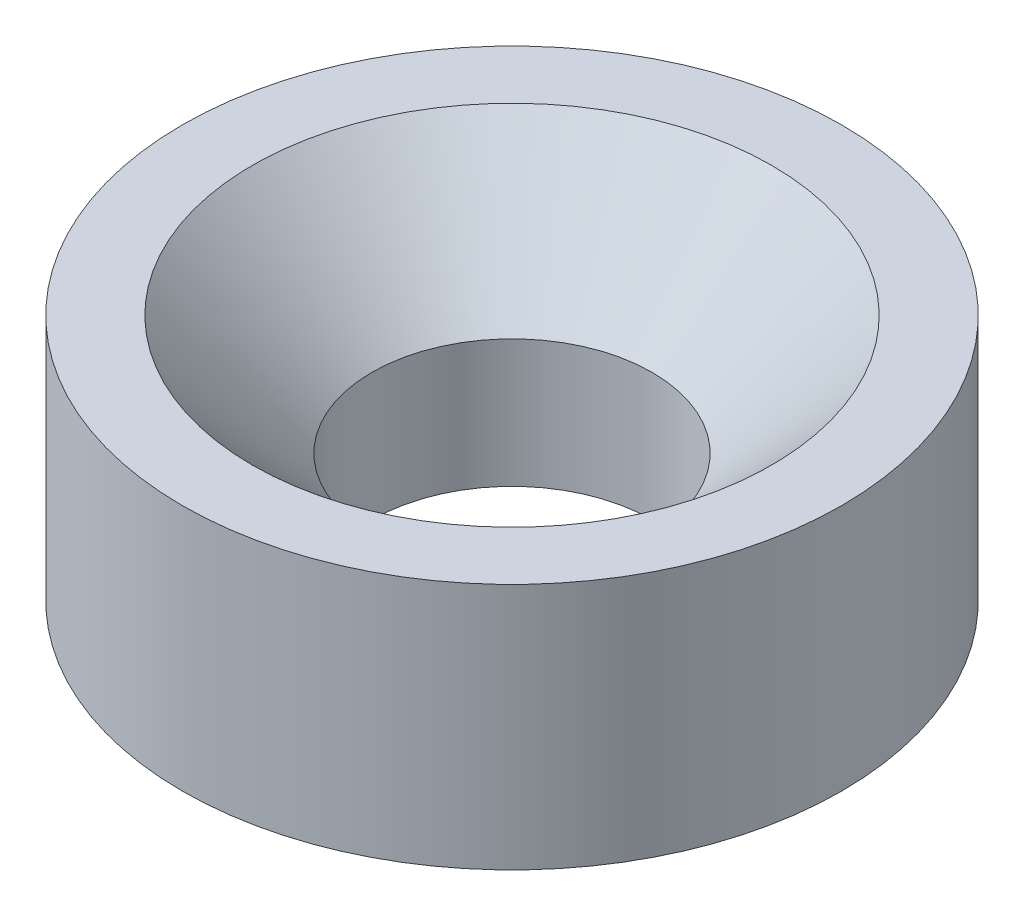
SolidWorks part; units mm, degrees
ref_plane "Front Plane" through (0, 0, 0) normal (0, 0, 1) x (1, 0, 0)
ref_plane "Top Plane" through (0, 0, 0) normal (0, 1, 0) x (1, 0, 0)
ref_plane "Right Plane" through (0, 0, 0) normal (1, 0, 0) x (0, 0, -1)
sketch "Sketch1" plane through (0, 0, 0) normal (0, 1, 0) x (1, 0, 0)
  circle A0 centre (0, 0) radius 4
  dimension "D1" = 8
extrude "Boss-Extrude1" add sketch "Sketch1" along normal blind 3
hole_wizard "CSK for M3 Countersunk Flat Head Screw1" positions "Sketch2" profile "Sketch3" countersink size "M3" standard "DIN" end condition through all
sketch "Sketch2" plane through (0, 3, 0) normal (0, 1, 0) x (1, 0, 0)
  point P0 (0, 0)
sketch "Sketch3" plane through (0, 3, 0) normal (1, 0, 0) x (0, 0, 1)
  line L0 (0, 0) -> (0, 3)
  line L1 (0, 3) -> (1.7, 3)
  line L2 (1.7, 3) -> (1.7, 1.45)
  line L3 (1.7, 1.45) -> (3.15, 0)
  line L5 (3.15, 0) -> (0, 0)
  line L6 (-1.7, 1.45) -> (-3.15, 0) construction
  line L11 (0, -6.35) -> (0, 107.95) construction
  dimension "Thru Hole Dia." = 3.4
  dimension "Thru Hole Depth" = 3
  dimension "Near C'Sink Dia." = 6.3
  dimension "Near C'Sink Angle" = 90
